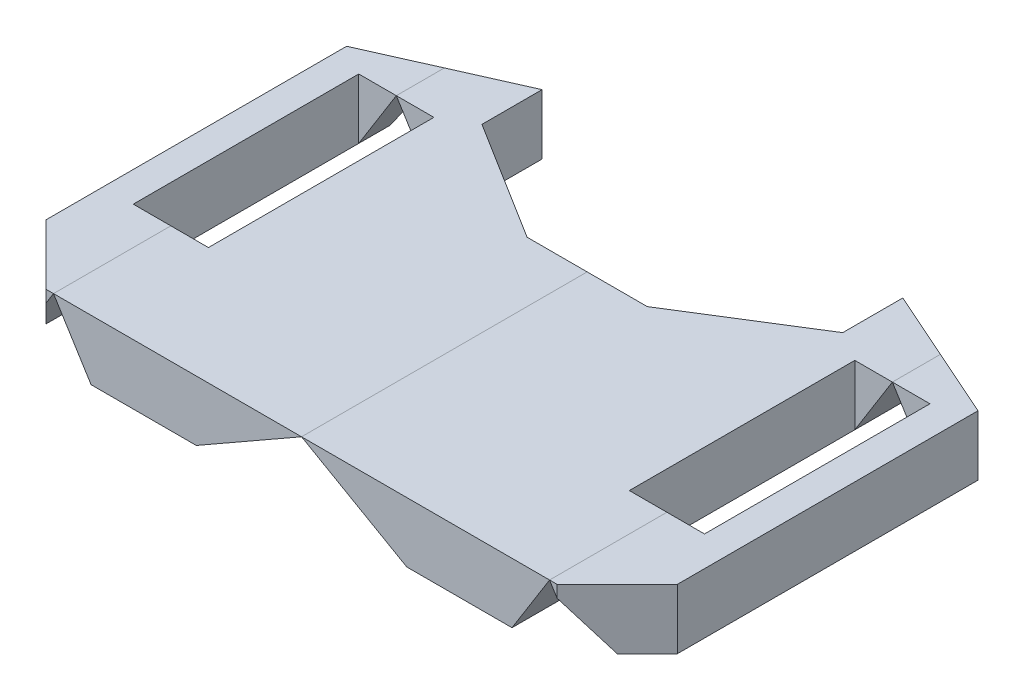
SolidWorks part; units mm, degrees
ref_plane "Front Plane" through (0, 0, 0) normal (0, 0, 1) x (1, 0, 0)
ref_plane "Top Plane" through (0, 0, 0) normal (0, 1, 0) x (1, 0, 0)
ref_plane "Right Plane" through (0, 0, 0) normal (1, 0, 0) x (0, 0, -1)
sketch "Sketch1" plane through (0, 0, 0) normal (0, 1, 0) x (1, 0, 0)
  line L28 (52.9999, -138.966) -> (116.4999, -138.966) construction
  line L29 (52.9999, -138.966) -> (52.9999, -329.466) construction
  line L30 (52.9999, -329.466) -> (116.4999, -329.466) construction
  line L31 (116.4999, -138.966) -> (116.4999, -329.466) construction
  line L32 (472.0999, -138.966) -> (472.0999, -329.466) construction
  line L33 (535.5999, -329.466) -> (472.0999, -329.466) construction
  line L34 (535.5999, -138.966) -> (535.5999, -329.466) construction
  line L35 (535.5999, -138.966) -> (472.0999, -138.966) construction
  line L36 (446.6999, -123.7874) -> (345.0999, -187.2874) construction
  line L37 (446.6999, -72.9874) -> (446.6999, -123.7874) construction
  line L38 (560.9999, -123.7874) -> (446.6999, -72.9874) construction
  line L39 (560.9999, -377.7874) -> (560.9999, -123.7874) construction
  line L40 (510.1999, -428.5874) -> (560.9999, -377.7874) construction
  line L41 (78.3999, -428.5874) -> (510.1999, -428.5874) construction
  line L42 (78.3999, -428.5874) -> (27.5999, -377.7874) construction
  line L43 (27.5999, -123.8483) -> (27.5999, -375.907) construction
  line L44 (27.5999, -123.7874) -> (141.8999, -72.9874) construction
  line L45 (141.8999, -72.9874) -> (141.8999, -123.7874) construction
  line L46 (141.8999, -123.7874) -> (243.4999, -187.2874) construction
  line L47 (345.0999, -187.2874) -> (243.4999, -187.2874) construction
  line L48 (52.9999, -138.966) -> (116.4999, -138.966)
  line L49 (52.9999, -138.966) -> (52.9999, -329.466)
  line L50 (52.9999, -329.466) -> (116.4999, -329.466)
  line L51 (116.4999, -138.966) -> (116.4999, -329.466)
  line L52 (472.0999, -138.966) -> (472.0999, -329.466)
  line L53 (535.5999, -329.466) -> (472.0999, -329.466)
  line L54 (535.5999, -138.966) -> (535.5999, -329.466)
  line L55 (535.5999, -138.966) -> (472.0999, -138.966)
  line L56 (446.6999, -123.7874) -> (345.0999, -187.2874)
  line L57 (446.6999, -72.9874) -> (446.6999, -123.7874)
  line L58 (560.9999, -123.7874) -> (446.6999, -72.9874)
  line L59 (560.9999, -377.7874) -> (560.9999, -123.7874)
  line L60 (510.1999, -428.5874) -> (560.9999, -377.7874)
  line L61 (78.3999, -428.5874) -> (510.1999, -428.5874)
  line L62 (78.3999, -428.5874) -> (27.5999, -377.7874)
  line L63 (27.5999, -123.8483) -> (27.5999, -375.907)
  line L64 (27.5999, -123.7874) -> (141.8999, -72.9874)
  line L65 (141.8999, -72.9874) -> (141.8999, -123.7874)
  line L66 (141.8999, -123.7874) -> (243.4999, -187.2874)
  line L67 (345.0999, -187.2874) -> (243.4999, -187.2874)
  line L68 (27.5999, -377.7874) -> (27.5999, -375.907)
  line L69 (27.5999, -123.8483) -> (27.5999, -123.7874)
extrude "Boss-Extrude1" add sketch "Sketch1" against normal blind 50.8
sketch "Sketch2" plane through (0, 0, 0) normal (0, 0, 1) x (1, 0, 0)
  line L0 (294.2999, 0) -> (294.2999, 50000) construction
  line L1 (78.3999, 0) -> (510.1999, 0) construction
  line L14 (472.0999, 0) -> (535.5999, 0) construction
  line L15 (52.9999, 0) -> (116.4999, 0) construction
  line L16 (472.0999, 0) -> (535.5999, 0) construction
  line L17 (52.9999, 0) -> (116.4999, 0) construction
  line L18 (52.9999, 0) -> (52.9999, -50.8) construction
  line L19 (116.4999, 0) -> (116.4999, -50.8) construction
  line L20 (472.0999, 0) -> (472.0999, -50.8) construction
  line L21 (535.5999, 0) -> (535.5999, -50.8) construction
  line L22 (510.1999, -50.8) -> (560.9999, -50.8) construction
  line L23 (345.0999, 0) -> (243.4999, 0) construction
  line L24 (345.0999, 0) -> (243.4999, 0) construction
  line L25 (243.4999, 0) -> (243.4999, -50.8) construction
  line L26 (345.0999, 0) -> (345.0999, -50.8) construction
  line L27 (52.9999, -50.8) -> (84.7499, 0)
  line L28 (84.7499, 0) -> (116.4999, -50.8)
  line L29 (116.4999, -50.8) -> (52.9999, -50.8)
  line L30 (294.2999, 0) -> (205.3999, -50.8)
  line L31 (78.3999, -50.8) -> (510.1999, -50.8) construction
  line L32 (205.3999, -50.8) -> (383.1999, -50.8)
  line L33 (294.2999, 0) -> (383.1999, -50.8)
  line L34 (472.0999, -50.8) -> (535.5999, -50.8)
  line L35 (503.8499, 0) -> (472.0999, -50.8)
  line L36 (535.5999, -50.8) -> (503.8499, 0)
  point P4 (294.2999, 0)
  point P26 (294.2999, -50.8)
  dimension "D1" = 88.9
extrude "Cut-Extrude1" cut sketch "Sketch2" along normal through all
sketch "Sketch3" plane through (0, 0, 0) normal (0, 1, 0) x (1, 0, 0)
  line L1 (-27.9548, -40.3583) -> (618.3474, -40.3583)
  line L2 (-27.9548, -40.3583) -> (-27.9548, -468.3878)
  line L3 (-27.9548, -468.3878) -> (618.3474, -468.3878)
  line L4 (618.3474, -40.3583) -> (618.3474, -468.3878)
extrude "Cut-Extrude2" [suppressed] cut sketch "Sketch3" against normal blind 12.7
